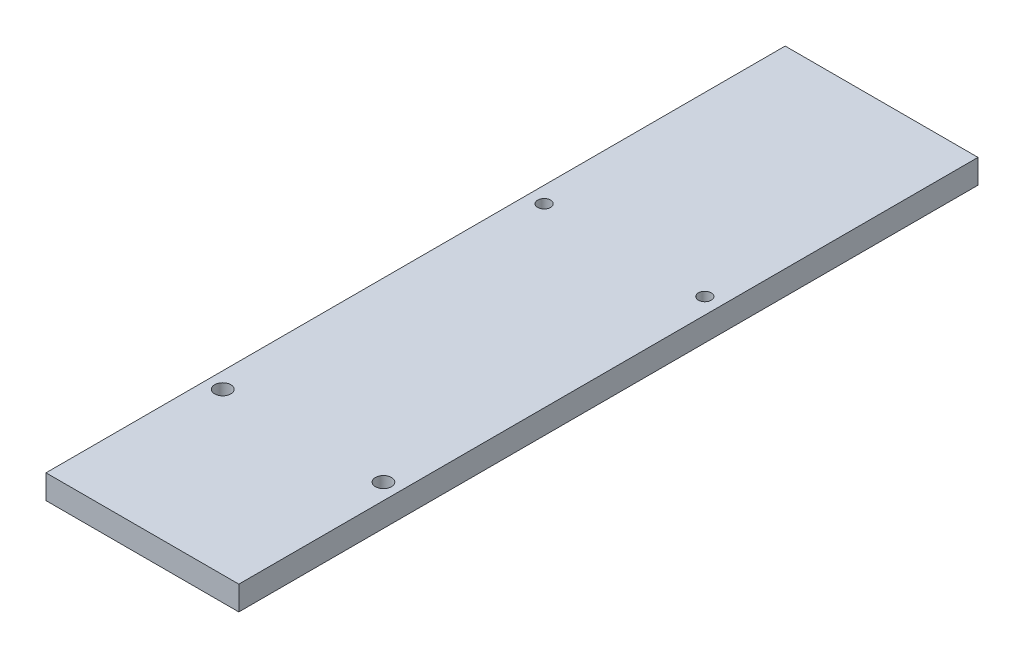
SolidWorks part; units mm, degrees
material "Cedar"
ref_plane "Front Plane" through (0, 0, 0) normal (0, 0, 1) x (1, 0, 0)
ref_plane "Top Plane" through (0, 0, 0) normal (0, 1, 0) x (1, 0, 0)
ref_plane "Right Plane" through (0, 0, 0) normal (1, 0, 0) x (0, 0, -1)
sketch "Sketch1" plane through (0, 0, 0) normal (0, 1, 0) x (1, 0, 0)
  line L1 (0, 0) -> (152.4, 0)
  line L2 (0, 0) -> (0, 584.2)
  line L3 (0, 584.2) -> (152.4, 584.2)
  line L4 (152.4, 0) -> (152.4, 584.2)
  dimension "D1" = 584.2
  dimension "D2" = 152.4
extrude "Boss-Extrude1" add sketch "Sketch1" along normal blind 19.05
sketch "Sketch2" plane through (0, 19.05, 0) normal (0, 1, 0) x (1, 0, 0)
  line L0 (152.4, 584.2) -> (0, 584.2) construction
  line L1 (0, 584.2) -> (0, 0) construction
  line L2 (152.4, 0) -> (152.4, 584.2) construction
  circle A0 centre (12.7, 381) radius 5.08
  circle A1 centre (139.7, 381) radius 5.08
  circle A2 centre (12.7, 127) radius 6.35
  circle A3 centre (139.7, 127) radius 6.35
  dimension "D1" = 10.16
  dimension "D5" = 12.7
  dimension "D7" = 12.7
  dimension "D2" = 203.2
  dimension "D3" = 12.7
  dimension "D4" = 12.7
  dimension "D6" = 254
  dimension "D8" = 12.7
extrude "Cut-Extrude1" cut sketch "Sketch2" against normal through all
